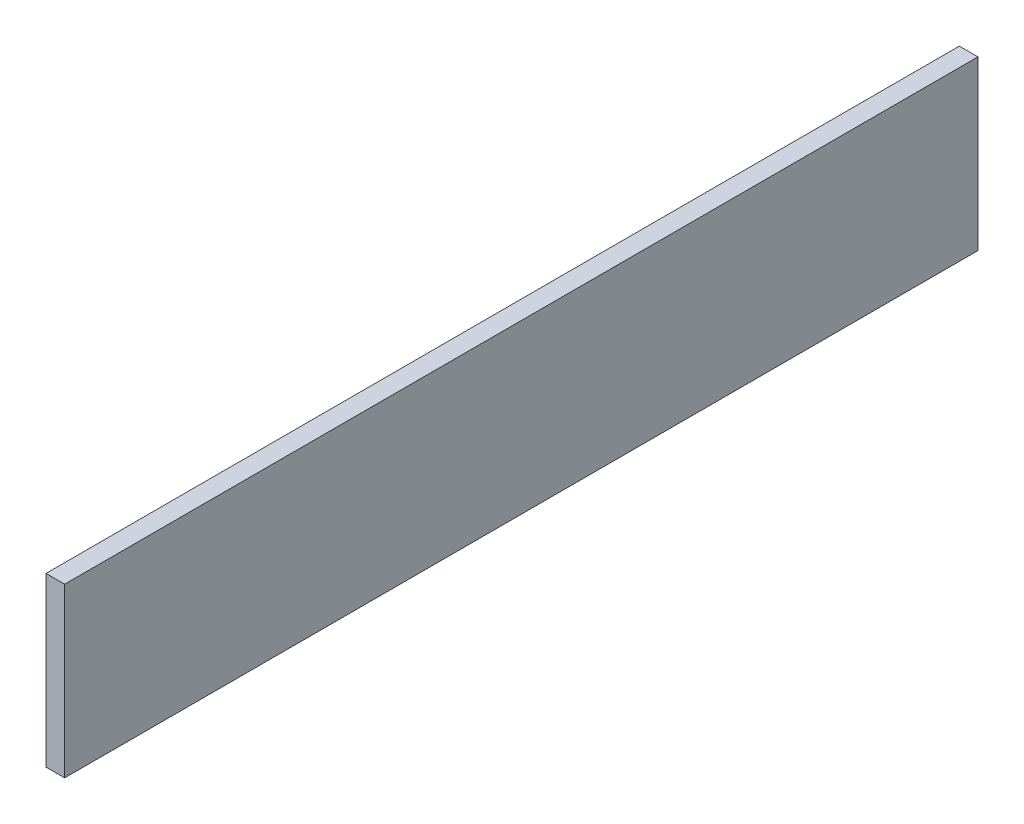
SolidWorks part; units mm, degrees
ref_plane "Front Plane" through (0, 0, 0) normal (0, 0, 1) x (1, 0, 0)
ref_plane "Top Plane" through (0, 0, 0) normal (0, 1, 0) x (1, 0, 0)
ref_plane "Right Plane" through (0, 0, 0) normal (1, 0, 0) x (0, 0, -1)
sketch "Sketch1" plane through (0, 0, 0) normal (1, 0, 0) x (0, 0, -1)
  line L1 (0, 0) -> (622.3, 0)
  line L2 (0, 0) -> (0, 114.3)
  line L3 (0, 114.3) -> (622.3, 114.3)
  line L4 (622.3, 0) -> (622.3, 114.3)
  dimension "D1" = 622.3
  dimension "D2" = 114.3
extrude "Boss-Extrude1" add sketch "Sketch1" along normal blind 12.7
